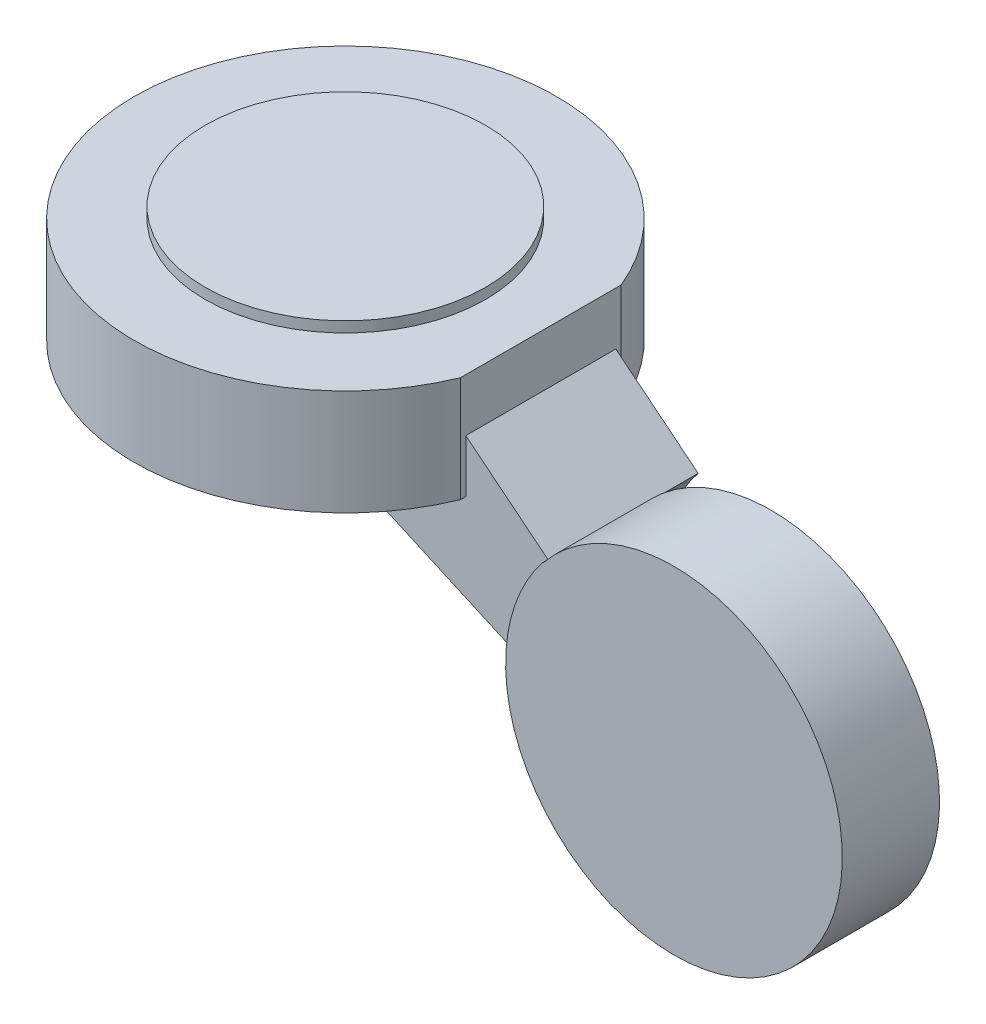
SolidWorks part; units mm, degrees
ref_plane "Front Plane" through (0, 0, 0) normal (0, 0, 1) x (1, 0, 0)
ref_plane "Top Plane" through (0, 0, 0) normal (0, 1, 0) x (1, 0, 0)
ref_plane "Right Plane" through (0, 0, 0) normal (1, 0, 0) x (0, 0, -1)
sketch "Sketch1" plane through (0, 0, 0) normal (0, 1, 0) x (1, 0, 0)
  circle A0 centre (0, 0) radius 200
extrude "Boss-Extrude1" add sketch "Sketch1" along normal blind 100 contours A0
sketch "Sketch2" plane through (0, 100, 0) normal (0, 1, 0) x (1, 0, 0)
  line L2 (185, 0) -> (185, 120.6425)
  line L3 (200, 0) -> (200, -137.8499)
  line L4 (200, -137.8499) -> (185, -137.8499)
  line L5 (185, -137.8499) -> (185, 0)
  line L6 (185, 120.6425) -> (192.5, 120.6425)
  line L7 (200, 0) -> (200, 120.6425)
  line L8 (200, 120.6425) -> (185, 120.6425)
  circle A0 centre (0, 0) radius 200 construction
  circle M1 centre (0, 0) radius 200
extrude "Cut-Extrude2" cut sketch "Sketch2" against normal blind 100 contours L5 L2 M1
sketch "Sketch4" plane through (0, 0, 0) normal (0, 0, 1) x (1, 0, 0)
  line L0 (185, 50) -> (185, 0)
  line L1 (387.0757, -112.9664) -> (251.9246, -112.9664)
  line L2 (251.9246, -112.9664) -> (0, 0)
  line L3 (185, 50) -> (387.0757, -112.9664)
  line L4 (185, 0) -> (185, 100) construction
  line L5 (185, 0) -> (0, 0)
extrude "Boss-Extrude2" add sketch "Sketch4" against normal up to vertex (75.9934 mm away)
sketch "Sketch7" plane through (0, 0, 0) normal (0, 0, 1) x (1, 0, 0)
  line L0 (0, 0) -> (185, 0)
  line L1 (185, 0) -> (185, 50)
  line L2 (185, 50) -> (387.0757, -112.9664)
  line L3 (387.0757, -112.9664) -> (251.9246, -112.9664)
  line L4 (251.9246, -112.9664) -> (0, 0)
extrude "Boss-Extrude3" add sketch "Sketch7" along normal up to vertex (75.9934 mm away)
sketch "Sketch9" plane through (0, 0, 75.9934) normal (0, 0, 1) x (1, 0, 0)
  circle A0 centre (387.0757, -112.9664) radius 159.375
extrude "Boss-Extrude4" add sketch "Sketch9" against normal up to vertex (151.9868 mm away) contours A0
sketch "Sketch11" plane through (0, 0, -75.9934) normal (0, 0, -1) x (-1, 0, 0)
  circle A1 centre (-387.0757, -112.9664) radius 159.375
extrude "Cut-Extrude3" cut sketch "Sketch11" against normal blind 60 contours A1
sketch "Sketch12" plane through (0, 0, 75.9934) normal (0, 0, 1) x (1, 0, 0)
  line L0 (0, 0) -> (228.0604, -102.2654)
  line L1 (0, 0) -> (185, 0)
  line L2 (185, 0) -> (185, 50)
  line L3 (185, 50) -> (263.0168, -12.9176)
  arc A1 (262.7709, -12.7193) -> (228.0604, -102.2654) centre (388.8324, -113.0847) ccw
  line M4 (185, 50) -> (185, 0)
  line M5 (185, 0) -> (0, 0)
  line M6 (0, 0) -> (228.0604, -102.2654)
extrude "Cut-Extrude4" cut sketch "Sketch12" against normal blind 5 contours A1 L3 M4 M5 M6
sketch "Sketch14" plane through (0, 0, -75.9934) normal (0, 0, -1) x (-1, 0, 0)
  line L0 (-228.0604, -102.2654) -> (0, 0)
  line L1 (0, 0) -> (-185, 0)
  line L2 (-185, 0) -> (-185, 50)
  line L3 (-185, 50) -> (-263.0168, -12.9176)
  arc A0 (-263.0168, -12.9176) -> (-228.0604, -102.2654) centre (-387.0757, -112.9664) cw
extrude "Cut-Extrude5" cut sketch "Sketch14" against normal blind 5
sketch "Sketch15" plane through (0, 0, -15.9934) normal (0, 0, -1) x (-1, 0, 0)
  circle A0 centre (-387.0757, -112.9664) radius 132.8125
extrude "Boss-Extrude5" add sketch "Sketch15" along normal blind 10
sketch "Sketch16" plane through (0, 100, 0) normal (0, 1, 0) x (1, 0, 0)
  circle A0 centre (0, 0) radius 132.8125
extrude "Boss-Extrude6" add sketch "Sketch16" along normal blind 10
